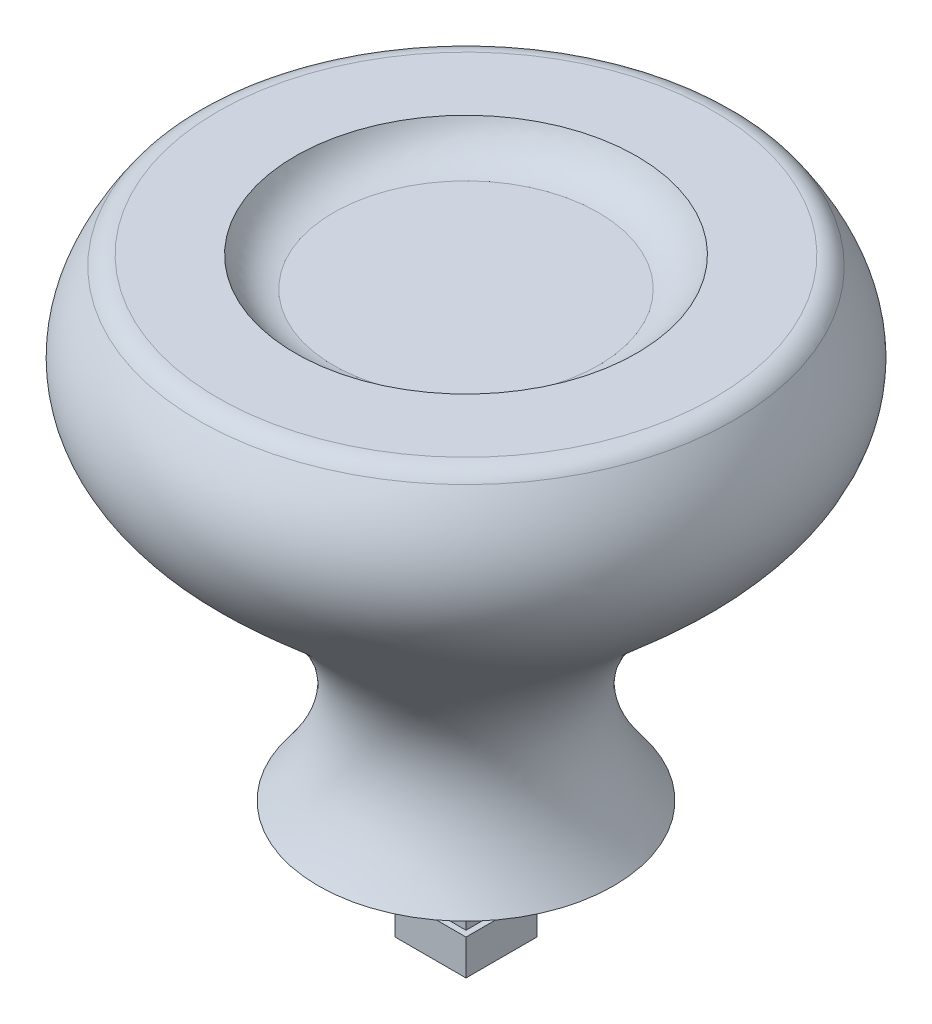
SolidWorks part; units mm, degrees
ref_plane "Plan de face" through (0, 0, 0) normal (0, 0, 1) x (1, 0, 0)
ref_plane "Plan de dessus" through (0, 0, 0) normal (0, 1, 0) x (1, 0, 0)
ref_plane "Plan de droite" through (0, 0, 0) normal (1, 0, 0) x (0, 0, -1)
sketch "Esquisse1" plane through (0, 0, 0) normal (0, 0, 1) x (1, 0, 0)
  line L0 (0, 0) -> (12.5, 0)
  line L1 (0, 0) -> (0, 40)
  line L2 (0, 40) -> (22, 40)
  spline S0 degree 3 poles (12.5, 0) (-2.793, 19.4776) (36.0482, 21.9036) (22, 40) knots 0 0 0 0 1 1 1 1
  point P4 (0, 0)
  point P11 (0, 40)
revolve "Révolution1" add sketch "Esquisse1" angle 360 about L1
sketch "Esquisse2" plane through (0, 0, 0) normal (0, 0, 1) x (1, 0, 0)
  line L0 (22, 40) -> (-22, 40) construction
  line L1 (0, -3.0458) -> (0, 41.6561) construction
  line L2 (-14.447, 40) -> (0, 40)
  line L3 (0, 40) -> (0, 37.487)
  line L4 (0, 37.487) -> (-11.2044, 37.487)
  spline S0 degree 2 poles (-14.447, 40) (-13.4766, 37.8769) (-11.2044, 37.487) knots 0 0 0 1 1 1
revolve "Enlèvement de matière-Révolution1" cut sketch "Esquisse2" angle 360 about L1
fillet "Congé2" radius 2 1 edges at (22, 40, 0)
sketch "Esquisse3" plane through (0, 0, 0) normal (0, -1, 0) x (1, 0, 0)
  line L1 (-2.5, 2.5) -> (2.5, 2.5)
  line L2 (-2.5, 2.5) -> (-2.5, -2.5)
  line L3 (-2.5, -2.5) -> (2.5, -2.5)
  line L4 (2.5, 2.5) -> (2.5, -2.5)
  line L5 (-2.5, 2.5) -> (2.5, -2.5) construction
  line L6 (-2.5, -2.5) -> (2.5, 2.5) construction
  point P0 (0, 0)
extrude "Boss.-Extru.1" add sketch "Esquisse3" along normal blind 10
sketch "Esquisse4" plane through (0, -10, 0) normal (0, -1, 0) x (1, 0, 0)
  line L1 (-3, -3) -> (3, -3)
  line L2 (-3, -3) -> (-3, 3)
  line L3 (-3, 3) -> (3, 3)
  line L4 (3, -3) -> (3, 3)
  line L5 (-3, -3) -> (3, 3) construction
  line L6 (-3, 3) -> (3, -3) construction
  point P0 (0, 0)
extrude "Boss.-Extru.2" add sketch "Esquisse4" against normal blind 3
